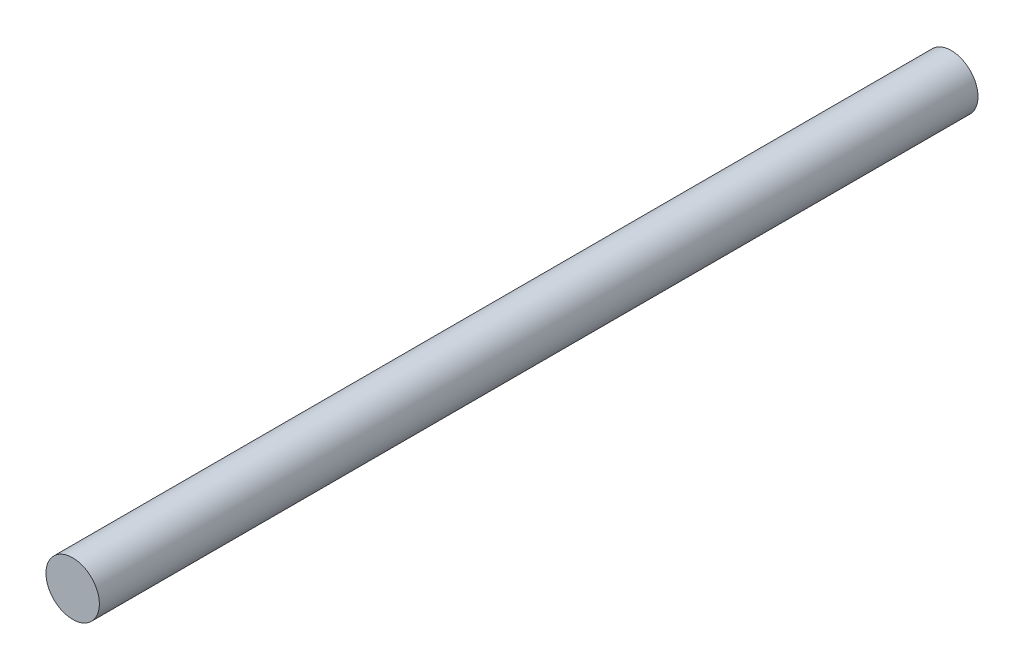
SolidWorks part; units mm, degrees
ref_plane "Front Plane" through (0, 0, 0) normal (0, 0, 1) x (1, 0, 0)
ref_plane "Top Plane" through (0, 0, 0) normal (0, 1, 0) x (1, 0, 0)
ref_plane "Right Plane" through (0, 0, 0) normal (1, 0, 0) x (0, 0, -1)
sketch "Sketch1" plane through (0, 0, 0) normal (0, 0, 1) x (1, 0, 0)
  circle A0 centre (0, 0) radius 2.25
  dimension "D1" = 4.5
extrude "Boss-Extrude1" add sketch "Sketch1" along normal blind 10 and the other way blind 64
sketch "Sketch2" plane through (0, 0, 0) normal (0, 0, 1) x (1, 0, 0)
  circle A0 centre (0, 0) radius 2.5 construction
  dimension "D1" = 5
